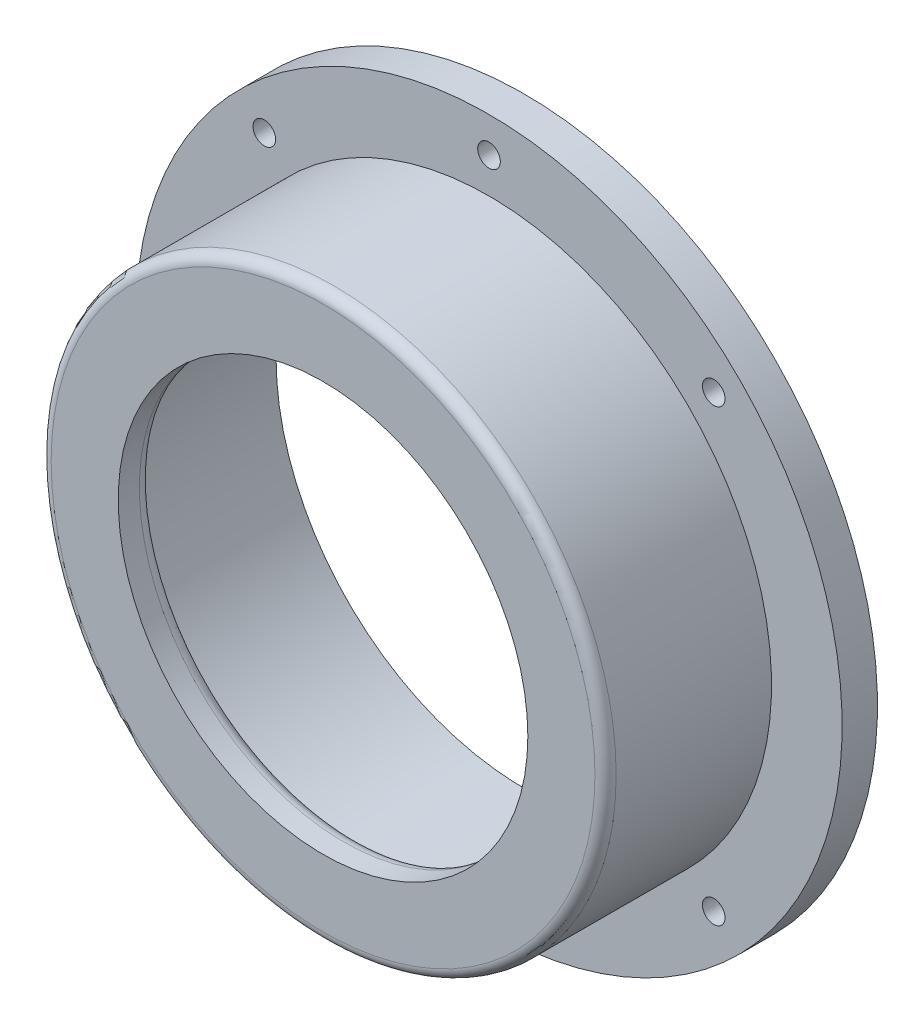
SolidWorks part; units mm, degrees
material "ABS"
ref_plane "前视基准面" through (0, 0, 0) normal (0, 0, 1) x (1, 0, 0)
ref_plane "上视基准面" through (0, 0, 0) normal (0, 1, 0) x (1, 0, 0)
ref_plane "右视基准面" through (0, 0, 0) normal (1, 0, 0) x (0, 0, -1)
sketch "草图1" plane through (0, 0, 0) normal (0, 0, 1) x (1, 0, 0)
  circle A0 centre (0, 0) radius 35.15
  circle A1 centre (0, 0) radius 40
  dimension "D1" = 70.3
  dimension "D2" = 80
extrude "凸台-拉伸1" add sketch "草图1" along normal blind 28.5
sketch "草图2" plane through (0, 0, 28.5) normal (0, 0, 1) x (1, 0, 0)
  circle A0 centre (0, 0) radius 35.5
  circle A1 centre (0, 0) radius 29
  dimension "D1" = 71
  dimension "D2" = 58
extrude "凸台-拉伸2" add sketch "草图2" against normal blind 5
sketch "草图3" plane through (0, 0, 0) normal (0, 0, -1) x (-1, 0, 0)
  circle A0 centre (0, 0) radius 40
  circle A1 centre (0, 0) radius 50
  dimension "D1" = 80
  dimension "D2" = 100
extrude "凸台-拉伸3" add sketch "草图3" against normal blind 5
sketch "草图4" plane through (0, 0, 5) normal (0, 0, 1) x (1, 0, 0)
  line L0 (0, 0) -> (0, 45) construction
  line L1 (0, 0) -> (50, 0) construction
  line L2 (31.8198, 31.8198) -> (0, 0) construction
  circle A0 centre (0, 0) radius 45 construction
  circle A1 centre (0, 0) radius 50 construction
  circle A2 centre (31.8198, 31.8198) radius 1.6
  circle A3 centre (31.8198, -31.8198) radius 1.6
  circle A4 centre (-31.8198, -31.8198) radius 1.6
  circle A5 centre (-31.8198, 31.8198) radius 1.6
  circle A6 centre (0, 45) radius 1.6
  circle A7 centre (0, -45) radius 1.6
  point P19 (0, 0)
  dimension "D1" = 90
  dimension "D2" = 45
  dimension "D3" = 3.2
  dimension "D5" = 3.2
  dimension "D4" = 4
extrude "切除-拉伸1" cut sketch "草图4" against normal through all
fillet "圆角1" radius 1.5 2 edges at (35.15, 0, 23.5) (40, 0, 28.5)
fillet "圆角2" radius 2 1 edges at (29, 0, 23.5)
